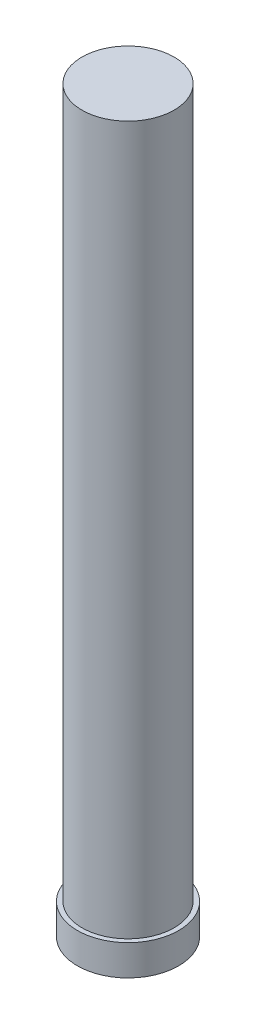
SolidWorks part; units mm, degrees
ref_plane "Alzado" through (0, 0, 0) normal (0, 0, 1) x (1, 0, 0)
ref_plane "Planta" through (0, 0, 0) normal (0, 1, 0) x (1, 0, 0)
ref_plane "Vista lateral" through (0, 0, 0) normal (1, 0, 0) x (0, 0, -1)
sketch "Croquis2" plane through (0, 0, 0) normal (1, 0, 0) x (0, 0, -1)
  line L0 (-377.6169, 0) -> (-427.6169, 0)
  line L1 (-427.6169, 0) -> (-427.6169, 800)
  line L2 (-427.6169, 800) -> (-377.6169, 800)
  line L3 (-377.6169, 800) -> (-377.6169, 0)
  line L4 (-377.6169, -122.4944) -> (-377.6169, 1080.1782) construction
  dimension "D1" = 800
  dimension "D2" = 50
revolve "Revolución1" add sketch "Croquis2" angle 360 about L4
sketch "Croquis3" plane through (0, 0, 0) normal (1, 0, 0) x (0, 0, -1)
  line L0 (-327.6169, 31.2351) -> (-322.6169, 31.2351)
  line L1 (-327.6169, 0) -> (-327.6169, 800) construction
  line L2 (-322.6169, 31.2351) -> (-322.6169, -1.9992)
  line L3 (-322.6169, -1.9992) -> (-377.6169, -1.9992)
  line L4 (-377.6169, -5.6247) -> (-377.6169, 31.2351) construction
  line L7 (-327.6169, 31.2351) -> (-327.6169, 0)
  line L8 (-327.6169, 0) -> (-377.6169, 0)
  line L9 (-427.6169, 0) -> (-327.6169, 0) construction
  line L10 (-377.6169, 0) -> (-377.6169, -1.9992)
  dimension "D1" = 5
revolve "Revolución2" add sketch "Croquis3" angle 360 about L4
